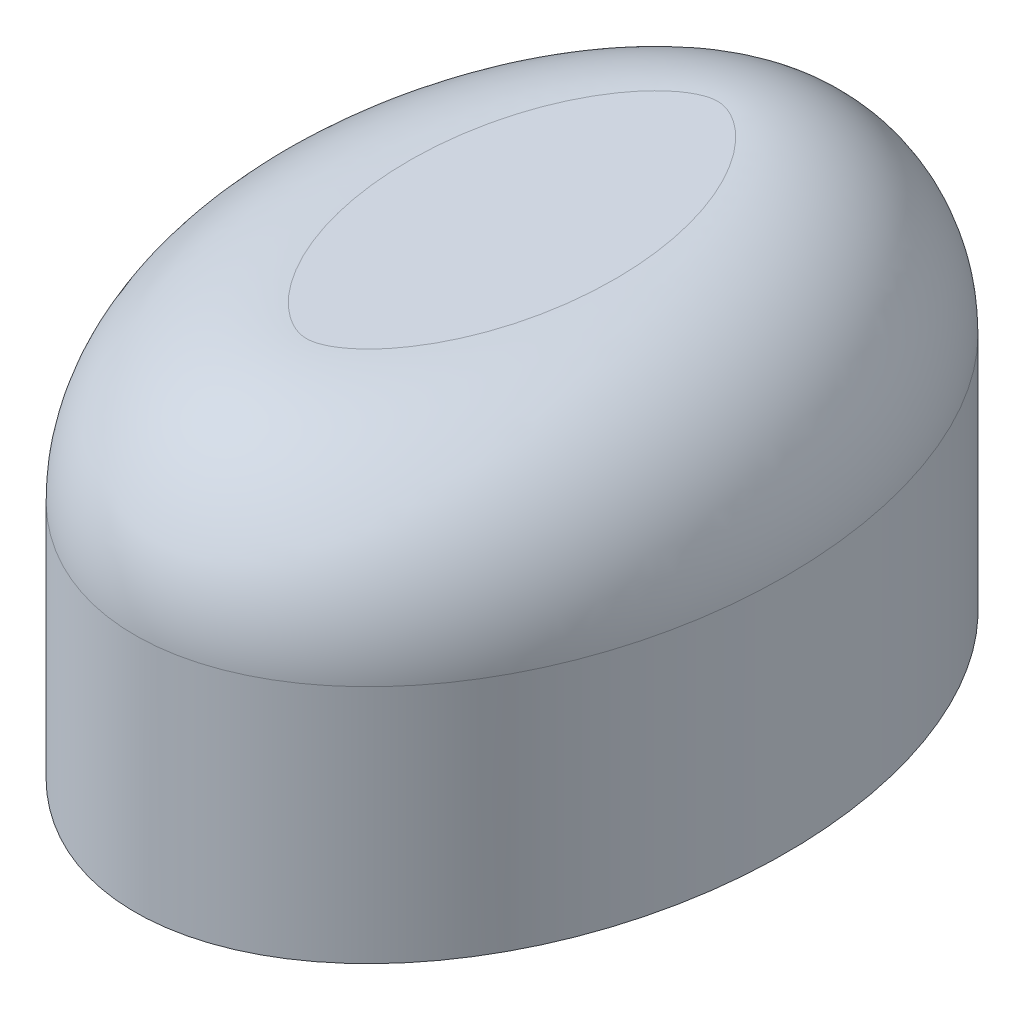
SolidWorks part; units mm, degrees
ref_plane "Front Plane" through (0, 0, 0) normal (0, 0, 1) x (1, 0, 0)
ref_plane "Top Plane" through (0, 0, 0) normal (0, 1, 0) x (1, 0, 0)
ref_plane "Right Plane" through (0, 0, 0) normal (1, 0, 0) x (0, 0, -1)
sketch "Sketch1" plane through (0, 0, 0) normal (0, 1, 0) x (1, 0, 0)
  ellipse E0 centre (0, 0) end of major axis (0, 2.75) minor radius 2
  dimension "D1" = 4
  dimension "D2" = 5.5
extrude "Boss-Extrude1" add sketch "Sketch1" along normal blind 3
fillet "Fillet1" radius 1.25 1 edges at (0, 3, -2.75)
